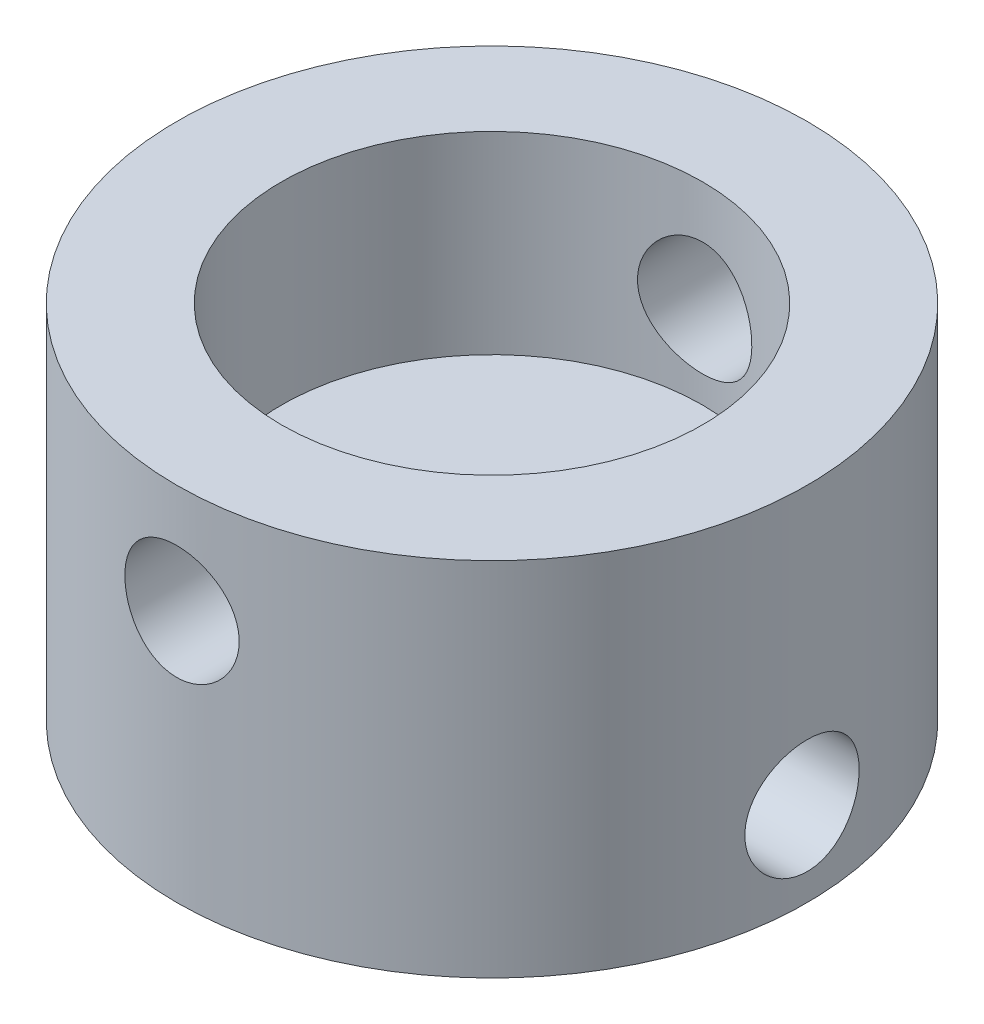
SolidWorks part; units mm, degrees
ref_plane "Front Plane" through (0, 0, 0) normal (0, 0, 1) x (1, 0, 0)
ref_plane "Top Plane" through (0, 0, 0) normal (0, 1, 0) x (1, 0, 0)
ref_plane "Right Plane" through (0, 0, 0) normal (1, 0, 0) x (0, 0, -1)
sketch "Sketch1" plane through (0, 0, 0) normal (0, 1, 0) x (1, 0, 0)
  circle A0 centre (0, 0) radius 2.9337
  circle A1 centre (0, 0) radius 9.525
  dimension "D1" = 5.8674
  dimension "D2" = 19.05
extrude "Boss-Extrude1" add sketch "Sketch1" along normal blind 5.08
sketch "Sketch2" plane through (0, 5.08, 0) normal (0, 1, 0) x (1, 0, 0)
  circle A0 centre (0, 0) radius 6.3627
  circle A1 centre (0, 0) radius 9.525
  dimension "D1" = 12.7254
  dimension "D2" = 19.05
extrude "Boss-Extrude2" add sketch "Sketch2" along normal blind 5.842
sketch "Sketch3" plane through (0, 0, 0) normal (0, 0, 1) x (1, 0, 0)
  line L1 (6.3627, 5.08) -> (-6.3627, 5.08) construction
  circle A1 centre (0, 7.62) radius 1.7272
  dimension "D3" = 2.54
  dimension "D1" = 3.4544
extrude "Cut-Extrude1" cut sketch "Sketch3" against normal mid plane 25.4
sketch "Sketch4" plane through (0, 0, 0) normal (1, 0, 0) x (0, 0, -1)
  line L0 (-9.525, 0) -> (9.525, 0) construction
  circle A0 centre (0, 2.54) radius 1.7272
  dimension "D2" = 3.4544
  dimension "D1" = 2.54
extrude "Cut-Extrude2" cut sketch "Sketch4" against normal mid plane 25.4
sketch "Sketch6" plane through (0, 5.08, 0) normal (0, 1, 0) x (1, 0, 0)
  circle A0 centre (0, 0) radius 4.2317
  circle A3 centre (0, 0) radius 1.4224
  dimension "D1" = 2.8448
extrude "Boss-Extrude4" add sketch "Sketch6" against normal blind 0.762 contours A0
